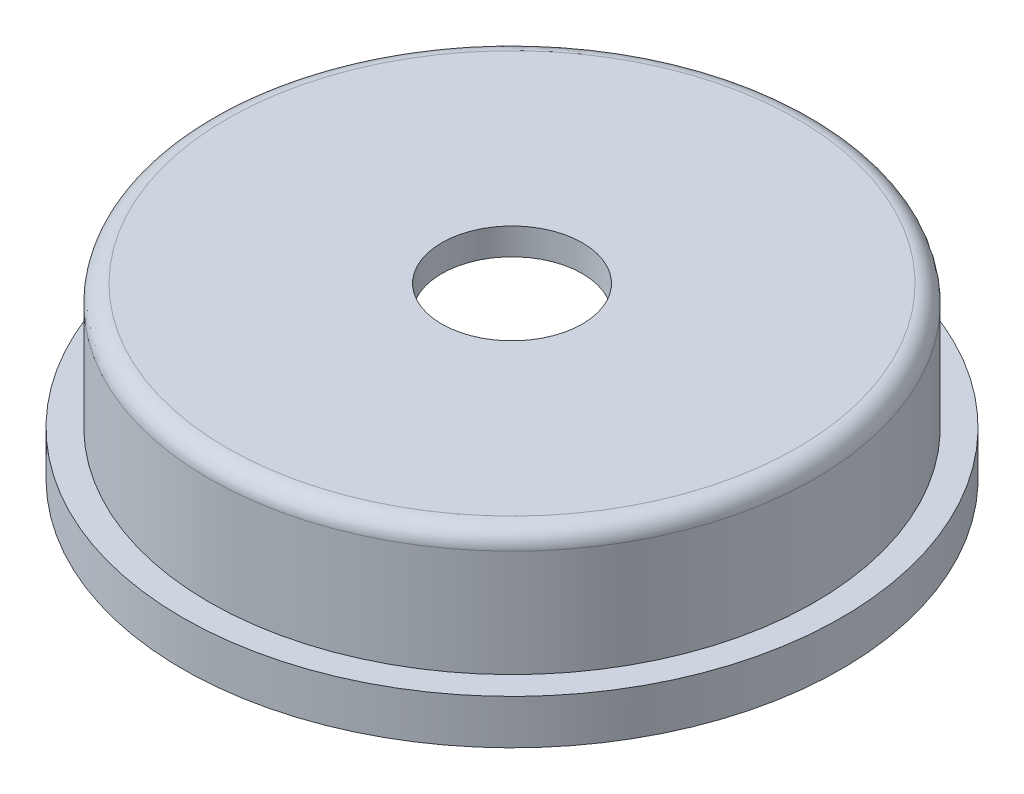
SolidWorks part; units mm, degrees
ref_plane "前视基准面" through (0, 0, 0) normal (0, 0, 1) x (1, 0, 0)
ref_plane "上视基准面" through (0, 0, 0) normal (0, 1, 0) x (1, 0, 0)
ref_plane "右视基准面" through (0, 0, 0) normal (1, 0, 0) x (0, 0, -1)
sketch "草图1" plane through (0, 0, 0) normal (0, 1, 0) x (1, 0, 0)
  circle A0 centre (0, 0) radius 18.5
  dimension "D1" = 37
extrude "凸台-拉伸1" add sketch "草图1" along normal blind 20
sketch "草图2" plane through (0, 0, 0) normal (0, -1, 0) x (1, 0, 0)
  circle A0 centre (0, 0) radius 16
  dimension "D1" = 32
extrude "切除-拉伸1" cut sketch "草图2" against normal blind 6.5
sketch "草图3" plane through (0, 6.5, 0) normal (0, -1, 0) x (1, 0, 0)
  circle A0 centre (0, 0) radius 3.95
  dimension "D1" = 7.9
extrude "切除-拉伸2" cut sketch "草图3" against normal blind 7
sketch "草图4" plane through (0, 13.5, 0) normal (0, -1, 0) x (1, 0, 0)
  circle A0 centre (0, 0) radius 3
  dimension "D1" = 6
extrude "切除-拉伸3" cut sketch "草图4" against normal blind 17
sketch "草图5" plane through (0, 20, 0) normal (0, 1, 0) x (1, 0, 0)
  circle A0 centre (0, 0) radius 25.1461
  circle A1 centre (0, 0) radius 17
  dimension "D1" = 34
extrude "切除-拉伸4" cut sketch "草图5" against normal blind 19
sketch "草图6" plane through (0, 20, 0) normal (0, 1, 0) x (1, 0, 0)
  line L2 (-1, 15.4677) -> (-1, 5.4083)
  line L4 (1, 15.4677) -> (1, 5.4083)
  line L7 (-15.4677, 1) -> (-5.4083, 1)
  line L9 (-15.4677, -1) -> (-5.4083, -1)
  line L20 (-1, -5.4083) -> (-1, -15.4677)
  line L23 (1, -5.4083) -> (1, -15.4677)
  line L24 (5.4083, -1) -> (15.4677, -1)
  line L27 (5.4083, 1) -> (15.4677, 1)
  arc A0 (-15.4677, -1) -> (-1, -15.4677) centre (0, 0) ccw
  arc A1 (-1, 5.4083) -> (-5.4083, 1) centre (0, 0) ccw
  arc A2 (-5.4083, -1) -> (-1, -5.4083) centre (0, 0) ccw
  arc A3 (1, -5.4083) -> (5.4083, -1) centre (0, 0) ccw
  arc A4 (5.4083, 1) -> (1, 5.4083) centre (0, 0) ccw
  arc A5 (-1, 15.4677) -> (-15.4677, 1) centre (0, 0) ccw
  arc A6 (15.4677, 1) -> (1, 15.4677) centre (0, 0) ccw
  arc A7 (1, -15.4677) -> (15.4677, -1) centre (0, 0) ccw
  dimension "D1" = 11
  dimension "D3" = 31
  dimension "D2" = 2
  dimension "D4" = 2
extrude "切除-拉伸5" cut sketch "草图6" against normal blind 12
sketch "草图8" plane through (0, 0, 0) normal (0, 0, 1) x (1, 0, 0)
  line L0 (-17, 8) -> (-22.9651, 8) construction
  line L4 (-19.272, 8) -> (-19.272, 20.8218)
  line L5 (-15, 8) -> (-5.4083, 16)
  line L6 (17, 8) -> (-1, 8) construction
  line L8 (-5.4083, 8) -> (-5.4083, 20) construction
  line L9 (-17, 20) -> (-17, 1) construction
  line L10 (-17, 8) -> (-19.272, 8)
  line L11 (-5.4083, 16) -> (-5.4083, 20.8218)
  line L12 (-5.4083, 20.8218) -> (-19.272, 20.8218)
  line L13 (-15, 8) -> (-17, 8)
  dimension "D1" = 2
  dimension "D2" = 8
revolve "切除-旋转2" cut sketch "草图8" angle 360 about axis through (0, 13.5, 0) along (0, -1, 0)
fillet "圆角5" radius 1 1 edges at (0, 8, -17)
fillet "圆角7" radius 2 8 edges at (-1, 11.9618, 5.4083) (-5.4083, 11.9618, 1) (-5.4083, 11.9618, -1) (-1, 11.9618, -5.4083) (1, 11.9618, -5.4083) (5.4083, 11.9618, -1) (5.4083, 11.9618, 1) (1, 11.9618, 5.4083)
sketch "草图9" plane through (0, 20, 0) normal (0, 1, 0) x (1, 0, 0)
  circle A0 centre (0, 0) radius 5.4083
  circle A1 centre (0, 0) radius 4.5
  dimension "D1" = 9
extrude "切除-拉伸6" cut sketch "草图9" against normal up to surface (4 mm away) up to face at (0, 16, 5.4083)
fillet "圆角8" radius 0.8 1 edges at (0, 20, 4.5)
sketch "草图10" plane through (0, 0, 0) normal (0, -1, 0) x (1, 0, 0)
  circle A0 centre (0, 0) radius 16
  circle A1 centre (0, 0) radius 18.5
extrude "凸台-拉伸2" add sketch "草图10" along normal blind 1.5
sketch "草图11" plane through (0, 8, 0) normal (0, 1, 0) x (1, 0, 0)
  circle A0 centre (0, 0) radius 16
extrude "切除-拉伸7" cut sketch "草图11" along normal through all
